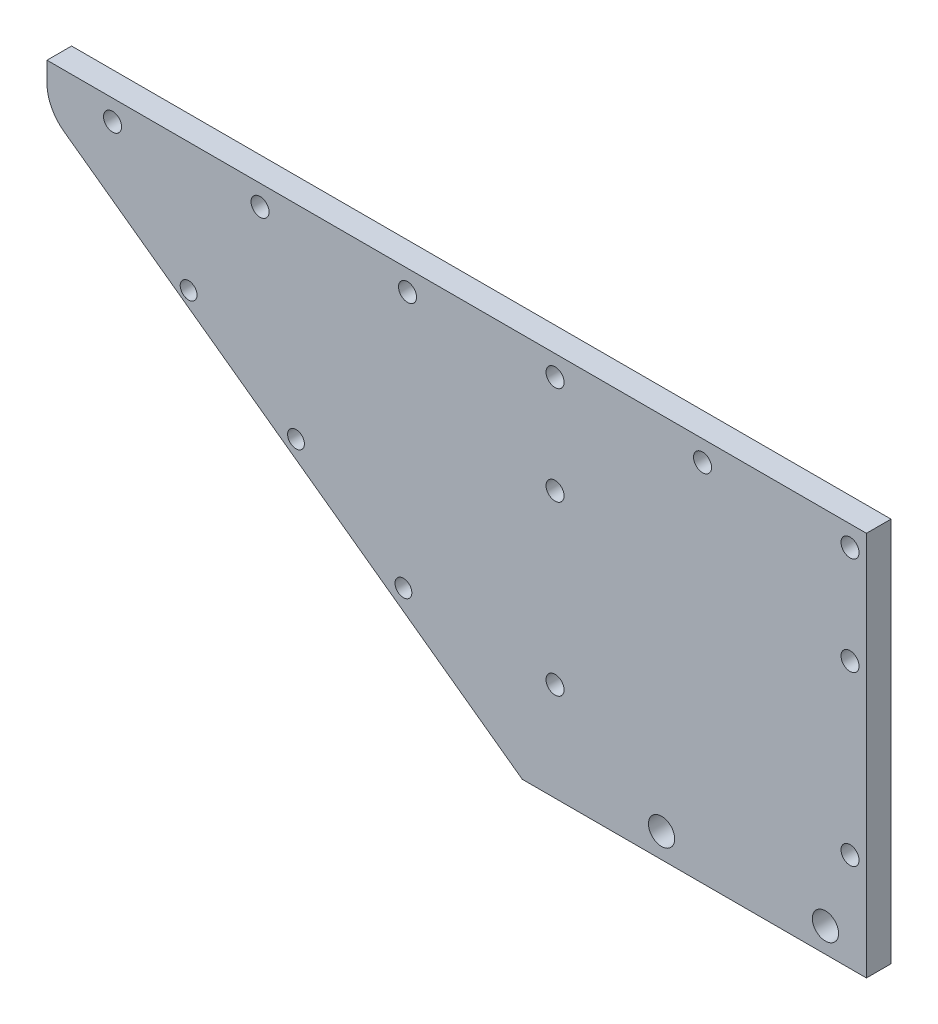
SolidWorks part; units mm, degrees
material "Thornel Mat VMA"
ref_plane "Front" through (0, 0, 0) normal (0, 0, 1) x (1, 0, 0)
ref_plane "Top" through (0, 0, 0) normal (0, 1, 0) x (1, 0, 0)
ref_plane "Right" through (0, 0, 0) normal (1, 0, 0) x (0, 0, -1)
sketch "草图1" plane through (0, 0, 0) normal (0, 0, 1) x (1, 0, 0)
  line L0 (0, 0) -> (0, -47)
  line L1 (0, -47) -> (-42, -47)
  line L2 (-42, -47) -> (-100, -5)
  line L3 (-100, -5) -> (-100, 0)
  line L4 (-100, 0) -> (0, 0)
  dimension "D1" = 47
  dimension "D2" = 100
  dimension "D3" = 42
  dimension "D4" = 5
extrude "凸台-拉伸1" add sketch "草图1" along normal blind 3
sketch "草图2" plane through (0, 0, 3) normal (0, 0, 1) x (1, 0, 0)
  line L0 (0, -47) -> (0, 0) construction
  line L1 (-20, 0) -> (-20, -50000) construction
  line L2 (0, 0) -> (-100, 0) construction
  line L3 (-42, -47) -> (0, -47) construction
  line L4 (-2, -2.5) -> (-100.0424, -2.5) construction
  line L5 (-2, -2.5) -> (-2, -44) construction
  line L6 (-2, -44) -> (-42.7329, -44) construction
  line L7 (-42.7329, -44) -> (-100.0424, -2.5) construction
  line L8 (-100, -5) -> (-42, -47) construction
  circle A0 centre (-38, -35) radius 1.1
  circle A1 centre (-38, -14.5) radius 1.1
  circle A2 centre (-38, -2.5) radius 1.1
  circle A3 centre (-56, -2.5) radius 1.1
  circle A4 centre (-74, -2.5) radius 1.1
  circle A5 centre (-92, -2.5) radius 1.1
  circle A6 centre (-56.5019, -34.0293) radius 1.025
  circle A7 centre (-69.6096, -24.8539) radius 1.025
  circle A8 centre (-82.7173, -15.6785) radius 1.025
  circle A112 centre (-20, -2.5) radius 1.1
  circle A115 centre (-2, -2.5) radius 1.1
  circle A118 centre (-2, -14.5) radius 1.1
  circle A121 centre (-2, -35) radius 1.1
  circle A124 centre (-5, -44) radius 1.6
  circle A127 centre (-25, -44) radius 1.6
  dimension "D3" = 3.2
  dimension "D4" = 3.2
  dimension "D10" = 2.2
  dimension "D11" = 2.2
  dimension "D12" = 2.2
  dimension "D13" = 2.2
  dimension "D18" = 2.05
  dimension "D21" = 16
  dimension "D1" = 20
  dimension "D2" = 5
  dimension "D5" = 3
  dimension "D6" = 12
  dimension "D7" = 12
  dimension "D8" = 2.5
  dimension "D9" = 2
  dimension "D14" = 20.5
  dimension "D15" = 20
  dimension "D16" = 18
  dimension "D17" = 2
  dimension "D19" = 3
  dimension "D20" = 17
extrude "切除-拉伸2" cut sketch "草图2" against normal through all
fillet "圆角1" radius 5 1 edges at (-100, -5, 1.5)
